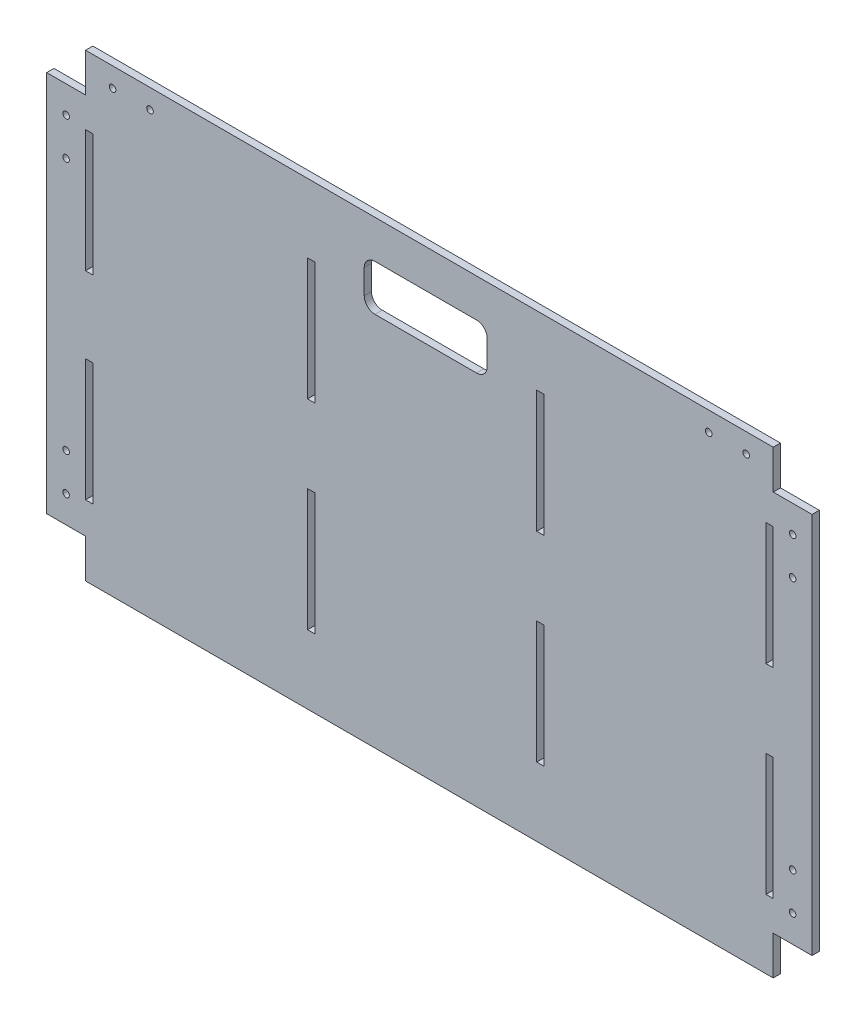
SolidWorks part; units mm, degrees
ref_plane "前基準面" through (0, 0, 0) normal (0, 0, 1) x (1, 0, 0)
ref_plane "上基準面" through (0, 0, 0) normal (0, 1, 0) x (1, 0, 0)
ref_plane "右基準面" through (0, 0, 0) normal (1, 0, 0) x (0, 0, -1)
sketch "草圖1" plane through (0, 0, 0) normal (0, 0, 1) x (1, 0, 0)
  line L1 (-250.4, 150.4) -> (250.4, 150.4)
  line L2 (-250.4, 150.4) -> (-250.4, -150.4)
  line L3 (-250.4, -150.4) -> (250.4, -150.4)
  line L4 (250.4, 150.4) -> (250.4, -150.4)
  line L5 (-250.4, 150.4) -> (250.4, -150.4) construction
  line L6 (-250.4, -150.4) -> (250.4, 150.4) construction
  point P0 (0, 0)
  dimension "D1" = 500.8
  dimension "D2" = 300.8
extrude "填料-伸長1" add sketch "草圖1" along normal blind 4.75 contours L1 L4 L3 L2
sketch "草圖2" plane through (0, 0, 0) normal (0, 0, -1) x (-1, 0, 0)
  line L0 (-225, 125) -> (-225, -125) construction
  line L1 (-250.4, 150.4) -> (-225, 150.4)
  line L2 (-250.4, 150.4) -> (-250.4, 125)
  line L3 (-250.4, 125) -> (-225, 125)
  line L4 (-225, 150.4) -> (-225, 125)
  line L5 (-250.4, -150.4) -> (-225, -150.4)
  line L6 (-250.4, -150.4) -> (-250.4, -125)
  line L7 (-250.4, -125) -> (-225, -125)
  line L8 (-225, -150.4) -> (-225, -125)
  line L9 (250.4, 150.4) -> (225, 150.4)
  line L10 (250.4, 150.4) -> (250.4, 125)
  line L12 (225, 150.4) -> (225, 125)
  line L13 (250.4, -150.4) -> (225, -150.4)
  line L14 (250.4, -150.4) -> (250.4, -125)
  line L16 (225, -150.4) -> (225, -125)
  line L18 (250.4, 150.4) -> (-250.4, 150.4) construction
  line L19 (-225, 105.4) -> (-220.25, 105.4)
  line L20 (-225, 105.4) -> (-225, 25.4)
  line L21 (-225, 25.4) -> (-220.25, 25.4)
  line L22 (-220.25, 105.4) -> (-220.25, 25.4)
  line L23 (-225, -25.4) -> (-220.25, -25.4)
  line L24 (-225, -25.4) -> (-225, -105.4)
  line L25 (-225, -105.4) -> (-220.25, -105.4)
  line L26 (-220.25, -25.4) -> (-220.25, -105.4)
  line L27 (250.4, -150.4) -> (-250.4, -150.4) construction
  line L44 (225, 105.4) -> (225, 25.4)
  line L45 (225, 105.4) -> (220.25, 105.4)
  line L46 (220.25, 105.4) -> (220.25, 25.4)
  line L47 (225, 25.4) -> (220.25, 25.4)
  line L48 (225, -24.4) -> (225, -104.4)
  line L49 (225, -24.4) -> (220.25, -24.4)
  line L50 (220.25, -24.4) -> (220.25, -104.4)
  line L51 (225, -104.4) -> (220.25, -104.4)
  line L60 (-75, 105.4) -> (-75, 25.4)
  line L61 (-75, 25.4) -> (-70.25, 25.4)
  line L62 (-70.25, 105.4) -> (-70.25, 25.4)
  line L63 (-75, 105.4) -> (-70.25, 105.4)
  line L80 (75, 105.4) -> (75, 25.4)
  line L81 (75, 25.4) -> (79.75, 25.4)
  line L82 (79.75, 105.4) -> (79.75, 25.4)
  line L83 (75, 105.4) -> (79.75, 105.4)
  line L84 (-250.4, 0) -> (250.4, 0) construction
  line L85 (-250.4, 150.4) -> (-250.4, -150.4) construction
  line L86 (250.4, 150.4) -> (250.4, -150.4) construction
  line L89 (250.4, -125) -> (250.4, 125)
  line L91 (250.4, 125) -> (250.4, -125)
  line L92 (75, -105.4) -> (79.75, -105.4)
  line L93 (79.75, -105.4) -> (79.75, -25.4)
  line L94 (75, -25.4) -> (79.75, -25.4)
  line L95 (75, -105.4) -> (75, -25.4)
  line L105 (-75, -105.4) -> (-70.25, -105.4)
  line L106 (-70.25, -105.4) -> (-70.25, -25.4)
  line L107 (-75, -25.4) -> (-70.25, -25.4)
  line L108 (-75, -105.4) -> (-75, -25.4)
  line L109 (225, 125) -> (250.4, 125)
  line L110 (225, -125) -> (250.4, -125)
  point P32 (0, 0)
  dimension "D1" = 25.4
  dimension "D2" = 25.4
  dimension "D3" = 25.4
  dimension "D4" = 25.4
  dimension "D5" = 25.4
  dimension "D6" = 25.4
  dimension "D7" = 25.4
  dimension "D8" = 25.4
  dimension "D9" = 4.75
  dimension "D10" = 80
  dimension "D11" = 45
  dimension "D12" = 4.75
  dimension "D13" = 80
  dimension "D14" = 45
  dimension "D15" = 4.75
  dimension "D16" = 4.75
  dimension "D17" = 25.4
  dimension "D18" = 25.4
  dimension "D19" = 250
  dimension "D20" = 25.4
  dimension "D21" = 4.75
extrude "除料-伸長1" cut sketch "草圖2" against normal blind 10
sketch "草圖3" plane through (0, 0, 4.75) normal (0, 0, 1) x (1, 0, 0)
  circle A0 centre (-237.7, 107.3) radius 2.15
  circle A1 centre (-237.7, 82.8) radius 2.15
  circle A2 centre (-207.3, 137.7) radius 2.15
  circle A3 centre (-182.8, 137.7) radius 2.15
  circle A4 centre (-237.7, -82.8) radius 2.15
  circle A5 centre (-237.7, -107.3) radius 2.15
  circle A10 centre (237.7, -107.3) radius 2.15
  circle A11 centre (237.7, -82.8) radius 2.15
  circle A12 centre (237.7, 107.3) radius 2.15
  circle A13 centre (237.7, 82.8) radius 2.15
  circle A14 centre (182.8, 137.7) radius 2.15
  circle A15 centre (207.3, 137.7) radius 2.15
extrude "除料-伸長2" cut sketch "草圖3" against normal blind 5
sketch "草圖4" plane through (0, 0, 4.75) normal (0, 0, 1) x (1, 0, 0)
  line L0 (-225, 150.4) -> (225, 150.4) construction
  line L2 (-75, 25.4) -> (-75, 105.4) construction
  line L8 (-42.625, 125.4) -> (37.875, 125.4)
  line L11 (-42.625, 125.4) -> (-42.625, 95.4)
  line L12 (-42.625, 95.4) -> (37.875, 95.4)
  line L13 (37.875, 125.4) -> (37.875, 95.4)
  line L14 (-42.625, 125.4) -> (37.875, 95.4) construction
  line L15 (-42.625, 95.4) -> (37.875, 125.4) construction
  point P0 (-2.375, 110.4)
  dimension "D1" = 25
  dimension "D2" = 30
  dimension "D3" = 80.5
  dimension "D4" = 32.375
extrude "除料-伸長3" cut sketch "草圖4" against normal blind 4.75
fillet "圓角1" radius 7 4 edges at (-42.625, 95.4, 2.375) (37.875, 95.4, 2.375) (37.875, 125.4, 2.375) (-42.625, 125.4, 2.375)
